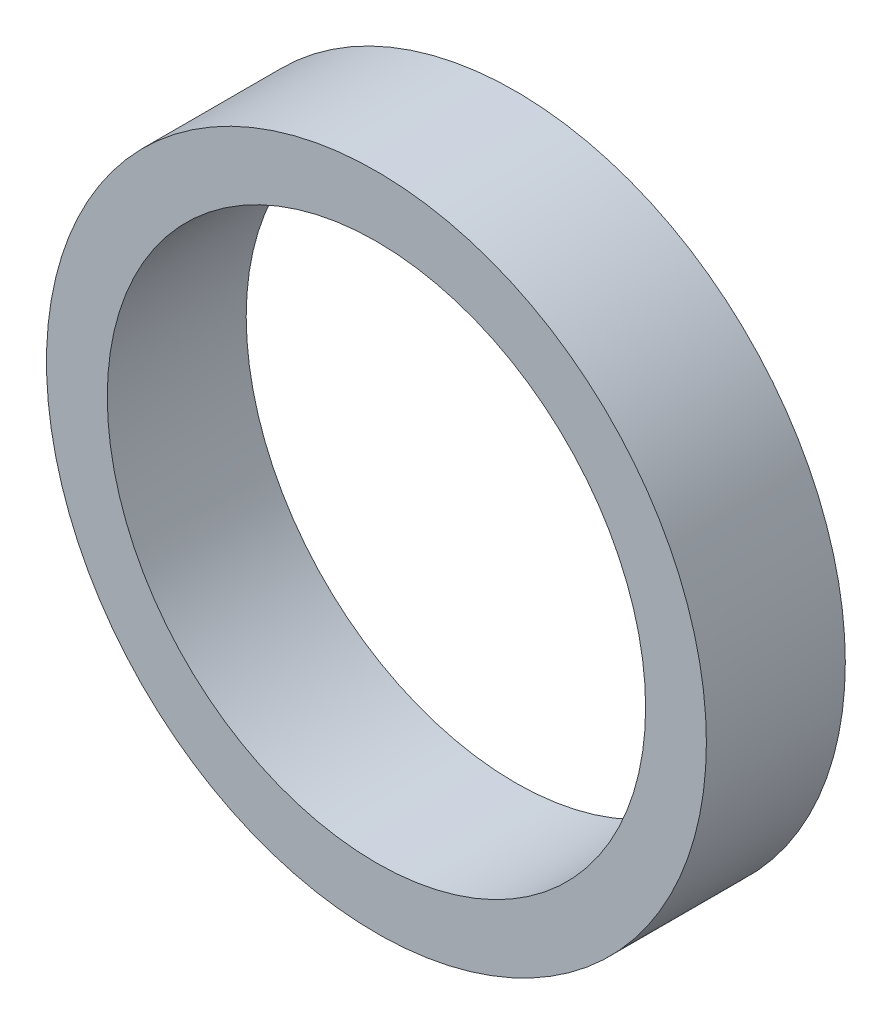
SolidWorks part; units mm, degrees
material "Custom Plastic"
ref_plane "Front Plane" through (0, 0, 0) normal (0, 0, 1) x (1, 0, 0)
ref_plane "Top Plane" through (0, 0, 0) normal (0, 1, 0) x (1, 0, 0)
ref_plane "Right Plane" through (0, 0, 0) normal (1, 0, 0) x (0, 0, -1)
sketch "Sketch1" plane through (0, 0, 0) normal (0, 0, 1) x (1, 0, 0)
  circle A0 centre (0, 0) radius 19
  circle A1 centre (0, 0) radius 15.5
  dimension "D1" = 38
  dimension "D2" = 31
extrude "Boss-Extrude1" add sketch "Sketch1" along normal blind 8
